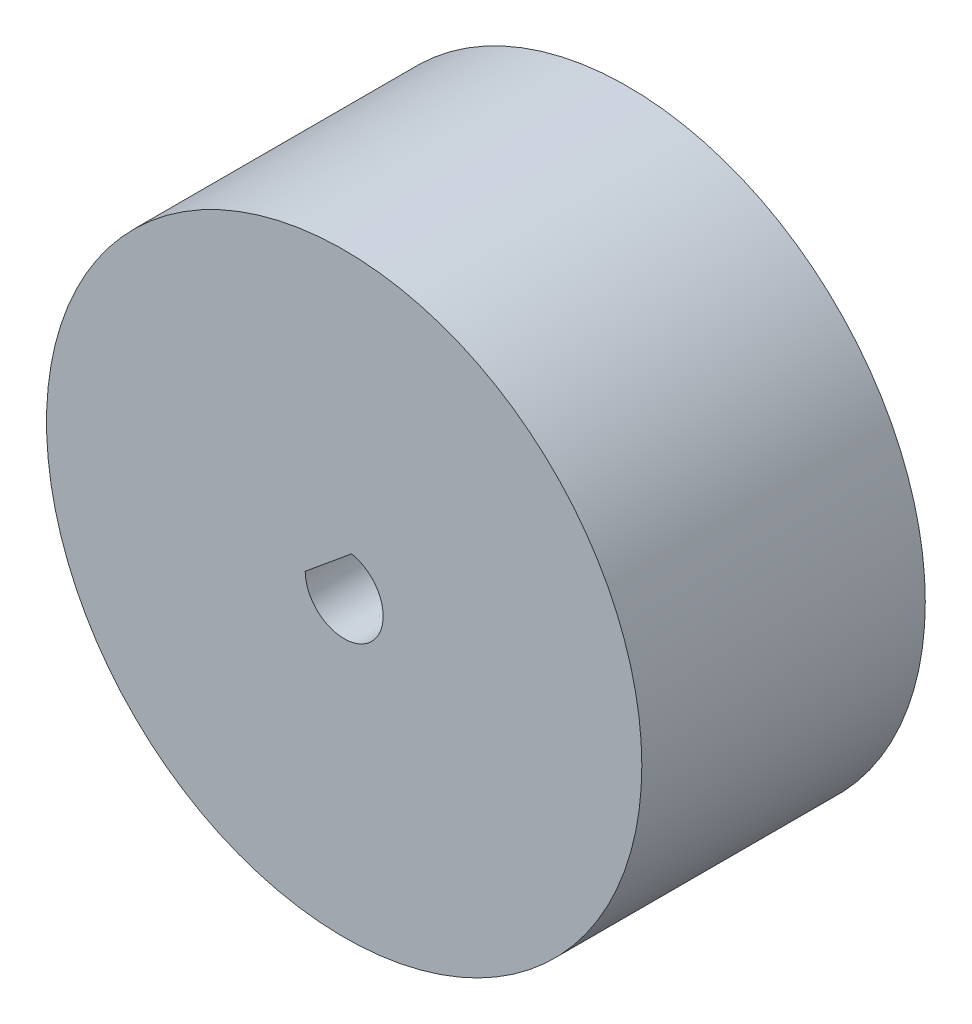
SolidWorks part; units mm, degrees
ref_plane "Front Plane" through (0, 0, 0) normal (0, 0, 1) x (1, 0, 0)
ref_plane "Top Plane" through (0, 0, 0) normal (0, 1, 0) x (1, 0, 0)
ref_plane "Right Plane" through (0, 0, 0) normal (1, 0, 0) x (0, 0, -1)
sketch "Sketch1" plane through (0, 0, 0) normal (0, 0, 1) x (1, 0, 0)
  circle A0 centre (0, 0) radius 21
  dimension "D1" = 42
extrude "Boss-Extrude1" add sketch "Sketch1" along normal blind 20
sketch "Sketch2" plane through (0, 0, 20) normal (0, 0, 1) x (1, 0, 0)
  line L3 (-2.75, 0) -> (0.5227, 2.6999)
  line L4 (0, -11) -> (0, 11) construction
  line L5 (11, 0) -> (-11, 0) construction
  arc A1 (0.5227, 2.6999) -> (-2.75, 0) centre (0, 0) cw
  point P7 (1.75, -2.1213)
  dimension "D3" = 2.75
  dimension "D1" = 0
  dimension "D2" = 0
  dimension "D4" = 4.5
  dimension "D5" = 0
extrude "Cut-Extrude1" cut sketch "Sketch2" against normal blind 17
sketch "Sketch3" plane through (0, 0, 20) normal (0, 0, 1) x (1, 0, 0)
  line L0 (0, -11) -> (0, 11) construction
  line L1 (11, 0) -> (-11, 0) construction
  circle A0 centre (0, 11.75) radius 4.25
  dimension "D1" = 8.5
  dimension "D2" = 11.75
extrude "Cut-Extrude2" cut sketch "Sketch3" against normal blind 18 from offset 3
